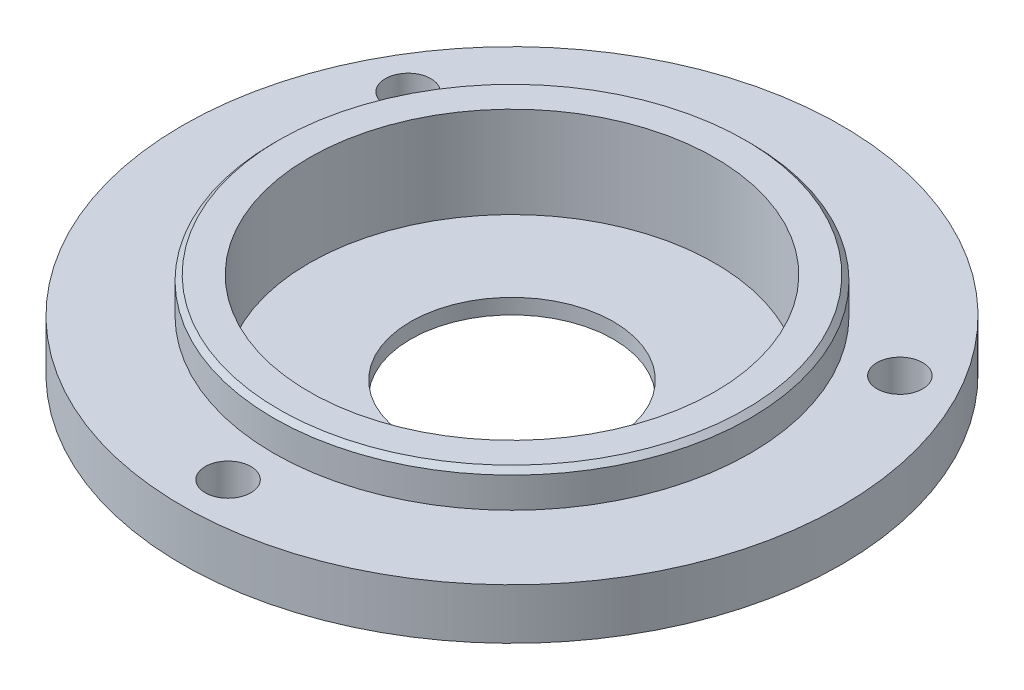
SolidWorks part; units mm, degrees
material "Alliage 1060"
ref_plane "Plan de face" through (0, 0, 0) normal (0, 0, 1) x (1, 0, 0)
ref_plane "Plan de dessus" through (0, 0, 0) normal (0, 1, 0) x (1, 0, 0)
ref_plane "Plan de droite" through (0, 0, 0) normal (1, 0, 0) x (0, 0, -1)
sketch "Esquisse1" plane through (0, 0, 0) normal (0, 0, 1) x (1, 0, 0)
  line L0 (0, 39.1071) -> (0, -39.828) construction
  line L1 (-10, -7) -> (-10, -5.5)
  line L2 (-10, -5.5) -> (-20, -5.5)
  line L3 (-20, -5.5) -> (-20, 3.5)
  line L4 (-20, 3.5) -> (-23, 3.5)
  line L5 (-23.5, 3) -> (-23.5, 0)
  line L6 (-23.5, 0) -> (-32.5, 0)
  line L7 (-32.5, 0) -> (-32.5, -5)
  line L8 (-32.5, -5) -> (-22, -5)
  line L9 (-22, -5) -> (-22, -7)
  line L10 (-22, -7) -> (-10, -7)
  line L11 (-23, 3.5) -> (-23.5, 3)
  point P5 (-23.5, 3.5)
  dimension "D1" = 47
  dimension "D2" = 20
  dimension "D3" = 65
  dimension "D4" = 40
  dimension "D5" = 3.5
  dimension "D6" = 5
  dimension "D7" = 9
  dimension "D8" = 7
  dimension "D9" = 22
  dimension "D10" = 0.5
  dimension "D11" = 45
revolve "Révolution1" add sketch "Esquisse1" angle 360 about L0
sketch "Esquisse2" plane through (0, 0, 0) normal (0, 1, 0) x (-1, 0, 0)
  circle A0 centre (0, 28) radius 2.25
  dimension "D1" = 4.5
  dimension "D2" = 28
extrude "Enlèv. mat.-Extru.1" cut sketch "Esquisse2" against normal through all
pattern_circular "Répétition circulaire1" count 3 every 120 about axis through (0, 0, 0) along (0, 1, 0) of "Enlèv. mat.-Extru.1"
